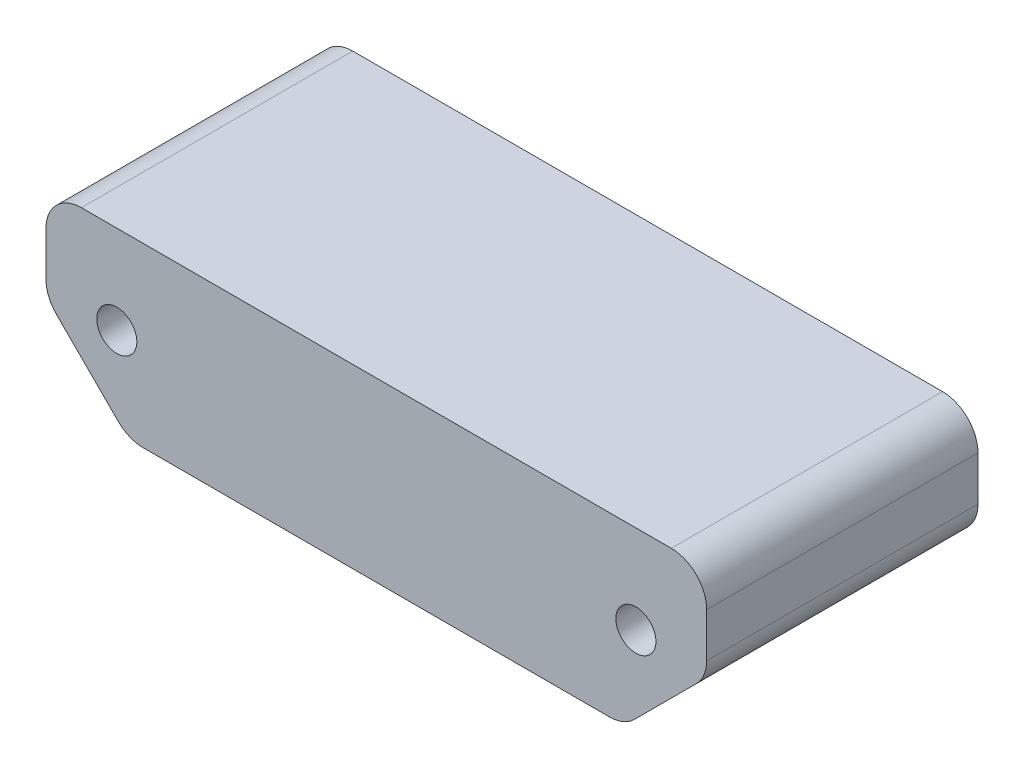
SolidWorks part; units mm, degrees
material "ABS"
ref_plane "前视基准面" through (0, 0, 0) normal (0, 0, 1) x (1, 0, 0)
ref_plane "上视基准面" through (0, 0, 0) normal (0, 1, 0) x (1, 0, 0)
ref_plane "右视基准面" through (0, 0, 0) normal (1, 0, 0) x (0, 0, -1)
other "Configuration Table"
sketch "草图1" plane through (0, 0, 0) normal (0, 0, 1) x (1, 0, 0)
  line L0 (-22, 0) -> (22, 0) construction
  line L1 (-28, -7.5) -> (28, -7.5)
  line L2 (-28, -7.5) -> (-28, 7.5)
  line L3 (-28, 7.5) -> (28, 7.5)
  line L4 (28, -7.5) -> (28, 7.5)
  line L5 (-28, -7.5) -> (28, 7.5) construction
  line L6 (-28, 7.5) -> (28, -7.5) construction
  line L7 (0, -7.5) -> (0, 7.5) construction
  circle A0 centre (22, 0) radius 1.7
  circle A1 centre (-22, 0) radius 1.7
  point P0 (0, 0)
  point P12 (0, 0)
  point P13 (0, 0)
  point P14 (0, 0)
  dimension "D4" = 3.4
  dimension "D1" = 56
  dimension "D2" = 15
  dimension "D3" = 44
extrude "凸台-拉伸1" add sketch "草图1" along normal blind 23
chamfer "倒角2" distance 7 angle 45 2 edges at (28, -7.5, 11.5) (-28, -7.5, 11.5)
fillet "圆角1" radius 3 6 edges at (21, -7.5, 11.5) (28, -0.5, 11.5) (28, 7.5, 11.5) (-28, 7.5, 11.5) (-21, -7.5, 11.5) (-28, -0.5, 11.5)
